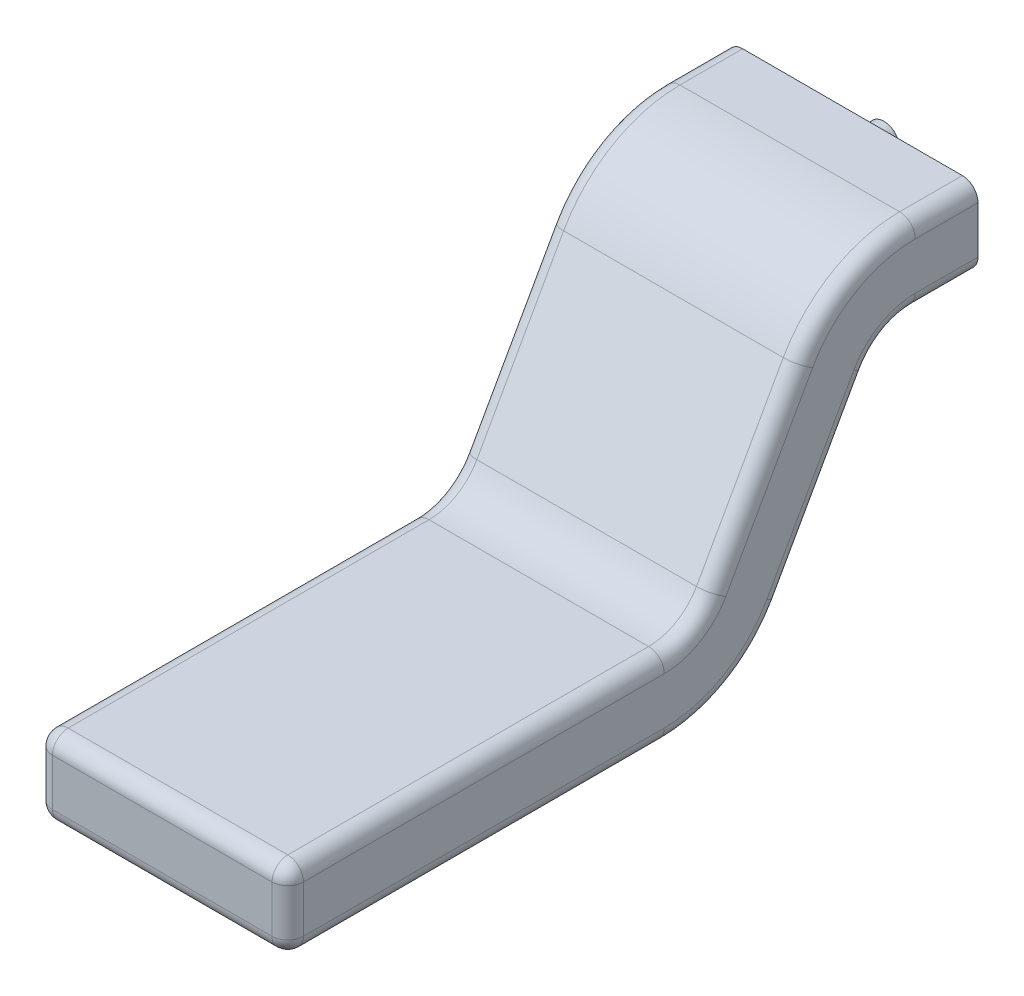
SolidWorks part; units mm, degrees
material "Liga 1060"
ref_plane "Plano frontal" through (0, 0, 0) normal (0, 0, 1) x (1, 0, 0)
ref_plane "Plano superior" through (0, 0, 0) normal (0, 1, 0) x (1, 0, 0)
ref_plane "Plano direito" through (0, 0, 0) normal (1, 0, 0) x (0, 0, -1)
sketch "Esboço1" plane through (0, 0, 0) normal (0, 0, 1) x (1, 0, 0)
  line L1 (-0.35, -0.125) -> (0.35, -0.125)
  line L2 (-0.4, -0.075) -> (-0.4, 0.075)
  line L3 (-0.35, 0.125) -> (0.35, 0.125)
  line L4 (0.4, -0.075) -> (0.4, 0.075)
  line L5 (-0.4, -0.125) -> (0.4, 0.125) construction
  line L6 (-0.4, 0.125) -> (0.4, -0.125) construction
  arc A0 (-0.35, 0.125) -> (-0.4, 0.075) centre (-0.35, 0.075) ccw
  arc A1 (-0.4, -0.075) -> (-0.35, -0.125) centre (-0.35, -0.075) ccw
  arc A2 (0.35, -0.125) -> (0.4, -0.075) centre (0.35, -0.075) ccw
  arc A3 (0.35, 0.125) -> (0.4, 0.075) centre (0.35, 0.075) cw
  point P0 (0, 0)
  dimension "D3" = 0.05
  dimension "D1" = 0.8
  dimension "D2" = 0.25
sketch "Esboço2" plane through (0, 0, 0) normal (1, 0, 0) x (0, 0, -1)
  line L0 (0, 0) -> (1.2, 0)
  line L1 (1.4617, 0.1533) -> (1.7383, 0.6467)
  line L2 (2, 0.8) -> (2.2, 0.8)
  arc A0 (1.2, 0) -> (1.4617, 0.1533) centre (1.2, 0.3) ccw
  arc A1 (2, 0.8) -> (1.7383, 0.6467) centre (2, 0.5) ccw
  point P7 (1.3757, 0)
  point P10 (1.8243, 0.8)
  dimension "D5" = 0.3
  dimension "D1" = 1.2
  dimension "D2" = 0.8
  dimension "D3" = 0.2
  dimension "D4" = 0.8
sweep "Varredura1" add profiles "Esboço1" path "Esboço2"
fillet "Filete2" radius 0.05 8 edges at (0, 0.125, 0) (0.3854, 0.1104, 0) (0.4, 0, 0) (0.3854, -0.1104, 0) (0, -0.125, 0) (-0.3854, -0.1104, 0) (-0.4, 0, 0) (-0.3854, 0.1104, 0)
sketch "Esboço3" plane through (0, 0, -2.2) normal (0, 0, -1) x (-1, 0, 0)
  line L0 (0, 0.785) -> (0, 0.635) construction
  line L5 (0.4, 0.875) -> (0.4, 0.725) construction
  line L6 (-0.4, 0.725) -> (-0.4, 0.875) construction
  line L7 (-0.2, 0.8) -> (0.2, 0.8) construction
  line L8 (-0.35, 0.925) -> (0.35, 0.925) construction
  line L9 (0.35, 0.675) -> (-0.35, 0.675) construction
  circle A0 centre (0, 0.8) radius 0.05
  dimension "D1" = 0.1
extrude "Ressalto-extrusão1" add sketch "Esboço3" along normal blind 0.1
